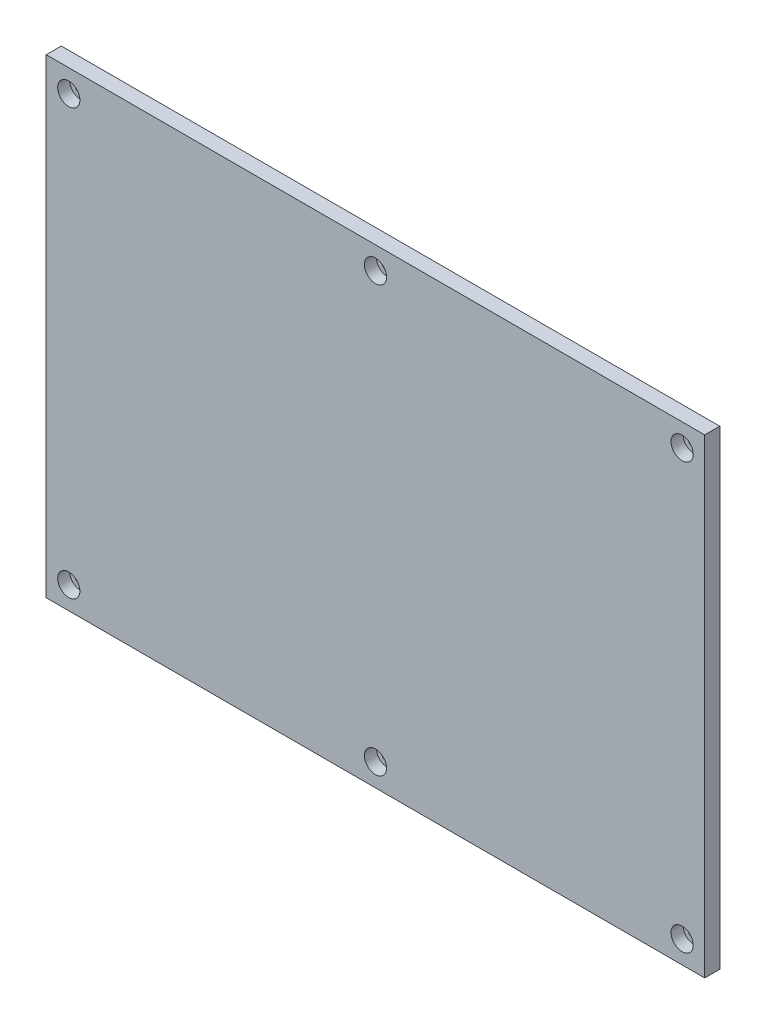
SolidWorks part; units mm, degrees
ref_plane "Front Plane" through (0, 0, 0) normal (0, 0, 1) x (1, 0, 0)
ref_plane "Top Plane" through (0, 0, 0) normal (0, 1, 0) x (1, 0, 0)
ref_plane "Right Plane" through (0, 0, 0) normal (1, 0, 0) x (0, 0, -1)
sketch "Sketch1" plane through (0, 0, 0) normal (0, 0, 1) x (1, 0, 0)
  line L1 (0, 0) -> (175, 0)
  line L2 (0, 0) -> (0, 125)
  line L3 (0, 125) -> (175, 125)
  line L4 (175, 0) -> (175, 125)
  dimension "D1" = 125
  dimension "D2" = 175
extrude "Boss-Extrude1" add sketch "Sketch1" along normal blind 4
sketch "Sketch2" plane through (0, 0, 4) normal (0, 0, 1) x (1, 0, 0)
  line L0 (175, 125) -> (0, 125) construction
  line L1 (0, 125) -> (0, 0) construction
  line L2 (175, 0) -> (175, 125) construction
  line L3 (0, 0) -> (175, 0) construction
  circle A0 centre (6, 119) radius 2.95
  circle A1 centre (169, 119) radius 2.95
  circle A2 centre (6, 6) radius 2.95
  circle A3 centre (169, 6) radius 2.95
  circle A4 centre (87.5, 119) radius 2.95
  circle A5 centre (87.5, 6) radius 2.95
  point P21 (87.5, 125)
  point P24 (87.5, 0)
  dimension "D1" = 5.9
  dimension "D2" = 5.9
  dimension "D3" = 5.9
  dimension "D4" = 5.9
  dimension "D5" = 5.9
  dimension "D6" = 5.9
  dimension "D7" = 6
  dimension "D8" = 6
  dimension "D9" = 6
  dimension "D10" = 6
  dimension "D11" = 6
  dimension "D12" = 6
  dimension "D13" = 6
  dimension "D14" = 6
  dimension "D15" = 6
  dimension "D16" = 6
extrude "Cut-Extrude1" cut sketch "Sketch2" against normal blind 3.2
sketch "Sketch3" plane through (0, 0, 0.8) normal (0, 0, 1) x (1, 0, 0)
  circle A0 centre (6, 119) radius 1.7
  circle A1 centre (87.5, 119) radius 1.7
  circle A2 centre (169, 119) radius 1.7
  circle A3 centre (169, 6) radius 1.7
  circle A4 centre (87.5, 6) radius 1.7
  circle A5 centre (6, 6) radius 1.7
  dimension "D1" = 3.4
  dimension "D2" = 3.4
  dimension "D3" = 3.4
  dimension "D4" = 3.4
  dimension "D5" = 3.4
  dimension "D6" = 3.4
extrude "Cut-Extrude2" cut sketch "Sketch3" against normal blind 3.2
